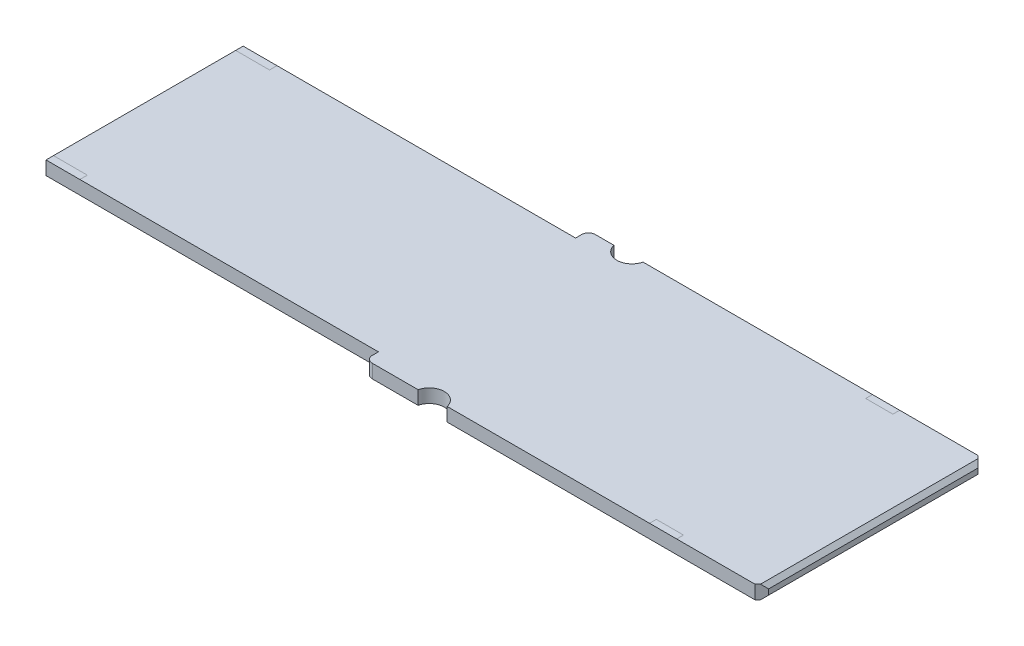
SolidWorks part; units mm, degrees
ref_plane "Front Plane" through (0, 0, 0) normal (0, 0, 1) x (1, 0, 0)
ref_plane "Top Plane" through (0, 0, 0) normal (0, 1, 0) x (1, 0, 0)
ref_plane "Right Plane" through (0, 0, 0) normal (1, 0, 0) x (0, 0, -1)
sketch "Sketch1" plane through (0, 0, 0) normal (0, 1, 0) x (1, 0, 0)
  line L0 (0, 7.25) -> (0, -7.25)
  line L1 (0, -7.25) -> (24.45, -7.25)
  line L2 (24.45, -7.25) -> (24.45, -8.2)
  line L3 (24.45, -8.2) -> (53.6, -8.2)
  line L4 (53.6, -8.2) -> (53.6, 8.2)
  line L5 (53.6, 8.2) -> (24.45, 8.2)
  line L6 (24.45, 7.25) -> (0, 7.25)
  line L7 (24.45, 8.2) -> (24.45, 7.25)
  dimension "D1" = 53.6
  dimension "D2" = 14.5
  dimension "D3" = 16.4
  dimension "D4" = 29.15
extrude "Boss-Extrude1" add sketch "Sketch1" along normal mid plane 1
chamfer "Chamfer2" [suppressed] distance 1 angle 45
chamfer "Chamfer3" distance 0.5 angle 45 2 edges at (53.6, 0, -8.2) (53.6, 0, 8.2)
sketch "Sketch2" plane through (0, -0.5, 0) normal (0, -1, 0) x (1, 0, 0)
  circle A0 centre (29.39, 8.45) radius 1.1
  circle A1 centre (27.39, -8.45) radius 1.1
  arc A2 (28.4317, 8.1643) -> (30.3483, 8.1643) centre (29.39, 8.45) ccw construction
  arc A3 (28.3483, -8.1643) -> (26.4317, -8.1643) centre (27.39, -8.45) ccw construction
  dimension "D1" = 2.2
extrude "Cut-Extrude1" cut sketch "Sketch2" against normal through all
sketch "Sketch3" plane through (0, 0.5, 0) normal (0, 1, 0) x (1, 0, 0)
  line L0 (53.6, -7.7) -> (53.6, 7.7) construction
  line L1 (53.6, 7.1) -> (45.6, 7.1)
  line L2 (53.6, 7.1) -> (53.6, 6.1)
  line L3 (53.6, 6.1) -> (45.6, 6.1)
  line L4 (45.6, 7.1) -> (45.6, 6.1)
  line L5 (53.1, 8.2) -> (28.4612, 8.2) construction
  dimension "D1" = 1
  dimension "D2" = 8
  dimension "D3" = 1.1
extrude "Cut-Extrude2" [suppressed] cut sketch "Sketch3" against normal blind 0.0001
pattern_linear "LPattern1" [suppressed] count 12 spacing 1.2
mirror "Mirror1" [suppressed] about plane through (0, 0, 0) normal (0, 1, 0)
sketch "Sketch4" plane through (0, -0.5, 0) normal (0, 1, 0) x (1, 0, 0)
  line L0 (25, 1.5) -> (25, -1.5) construction
  line L1 (23.5, 5) -> (26.5, 5)
  line L2 (23.5, 5) -> (23.5, 1.5)
  line L3 (23.5, 1.5) -> (26.5, 1.5)
  line L4 (26.5, 5) -> (26.5, 1.5)
  line L5 (23.5, -1.5) -> (26.5, -1.5)
  line L6 (23.5, -1.5) -> (23.5, -3.5)
  line L7 (23.5, -3.5) -> (26.5, -3.5)
  line L8 (26.5, -1.5) -> (26.5, -3.5)
  line L9 (25, 0) -> (0, 0) construction
  line L10 (7.45, 3.25) -> (23.5, 3.25) construction
  line L11 (4.45, 4.25) -> (7.45, 4.25)
  line L12 (4.45, 4.25) -> (4.45, 2.25)
  line L13 (4.45, 2.25) -> (7.45, 2.25)
  line L14 (7.45, 4.25) -> (7.45, 2.25)
  line L15 (0, 7.25) -> (0, -7.25) construction
  dimension "D1" = 3
  dimension "D2" = 3.5
  dimension "D3" = 2
  dimension "D4" = 3
  dimension "D5" = 25
  dimension "D6" = 4.45
extrude "Boss-Extrude2" [suppressed] add sketch "Sketch4" against normal blind 1
sketch "Sketch5" [suppressed] plane through (0, -0.525, 0) normal (0, 1, 0) x (1, 0, 0)
  line L0 (26.5, 1.5) -> (26.5, 5) construction
  line L1 (26.5, 5) -> (27.9, 5)
  line L2 (26.5, 5) -> (26.5, 4.7)
  line L3 (26.5, 4.7) -> (27.9, 4.7)
  line L4 (27.9, 5) -> (27.9, 4.7)
  line L5 (23.5, 5) -> (22.1, 5)
  line L6 (23.5, 5) -> (23.5, 4.7)
  line L7 (23.5, 4.7) -> (22.1, 4.7)
  line L8 (22.1, 5) -> (22.1, 4.7)
  line L9 (23.5, 5) -> (23.5, 1.5) construction
  line L10 (26.5, 4.6) -> (27.9, 4.6)
  line L11 (26.5, 4.6) -> (26.5, 4.3)
  line L12 (26.5, 4.3) -> (27.9, 4.3)
  line L13 (27.9, 4.6) -> (27.9, 4.3)
  line L14 (23.5, 4.6) -> (22.1, 4.6)
  line L15 (23.5, 4.6) -> (23.5, 4.3)
  line L16 (23.5, 4.3) -> (22.1, 4.3)
  line L17 (22.1, 4.6) -> (22.1, 4.3)
  line L18 (26.5, 4.2) -> (27.9, 4.2)
  line L19 (26.5, 4.2) -> (26.5, 3.9)
  line L20 (26.5, 3.9) -> (27.9, 3.9)
  line L21 (27.9, 4.2) -> (27.9, 3.9)
  line L22 (23.5, 4.2) -> (22.1, 4.2)
  line L23 (23.5, 4.2) -> (23.5, 3.9)
  line L24 (23.5, 3.9) -> (22.1, 3.9)
  line L25 (22.1, 4.2) -> (22.1, 3.9)
  line L26 (26.5, 3.8) -> (27.9, 3.8)
  line L27 (26.5, 3.8) -> (26.5, 3.5)
  line L28 (26.5, 3.5) -> (27.9, 3.5)
  line L29 (27.9, 3.8) -> (27.9, 3.5)
  line L30 (23.5, 3.8) -> (22.1, 3.8)
  line L31 (23.5, 3.8) -> (23.5, 3.5)
  line L32 (23.5, 3.5) -> (22.1, 3.5)
  line L33 (22.1, 3.8) -> (22.1, 3.5)
  line L34 (26.5, 3.4) -> (27.9, 3.4)
  line L35 (26.5, 3.4) -> (26.5, 3.1)
  line L36 (26.5, 3.1) -> (27.9, 3.1)
  line L37 (27.9, 3.4) -> (27.9, 3.1)
  line L38 (23.5, 3.4) -> (22.1, 3.4)
  line L39 (23.5, 3.4) -> (23.5, 3.1)
  line L40 (23.5, 3.1) -> (22.1, 3.1)
  line L41 (22.1, 3.4) -> (22.1, 3.1)
  line L42 (26.5, 3) -> (27.9, 3)
  line L43 (26.5, 3) -> (26.5, 2.7)
  line L44 (26.5, 2.7) -> (27.9, 2.7)
  line L45 (27.9, 3) -> (27.9, 2.7)
  line L46 (23.5, 3) -> (22.1, 3)
  line L47 (23.5, 3) -> (23.5, 2.7)
  line L48 (23.5, 2.7) -> (22.1, 2.7)
  line L49 (22.1, 3) -> (22.1, 2.7)
  line L50 (26.5, 2.6) -> (27.9, 2.6)
  line L51 (26.5, 2.6) -> (26.5, 2.3)
  line L52 (26.5, 2.3) -> (27.9, 2.3)
  line L53 (27.9, 2.6) -> (27.9, 2.3)
  line L54 (23.5, 2.6) -> (22.1, 2.6)
  line L55 (23.5, 2.6) -> (23.5, 2.3)
  line L56 (23.5, 2.3) -> (22.1, 2.3)
  line L57 (22.1, 2.6) -> (22.1, 2.3)
  line L58 (26.5, 2.2) -> (27.9, 2.2)
  line L59 (26.5, 2.2) -> (26.5, 1.9)
  line L60 (26.5, 1.9) -> (27.9, 1.9)
  line L61 (27.9, 2.2) -> (27.9, 1.9)
  line L62 (23.5, 2.2) -> (22.1, 2.2)
  line L63 (23.5, 2.2) -> (23.5, 1.9)
  line L64 (23.5, 1.9) -> (22.1, 1.9)
  line L65 (22.1, 2.2) -> (22.1, 1.9)
  line L66 (26.5, 1.8) -> (27.9, 1.8)
  line L67 (26.5, 1.8) -> (26.5, 1.5)
  line L68 (26.5, 1.5) -> (27.9, 1.5)
  line L69 (27.9, 1.8) -> (27.9, 1.5)
  line L70 (23.5, 1.8) -> (22.1, 1.8)
  line L71 (23.5, 1.8) -> (23.5, 1.5)
  line L72 (23.5, 1.5) -> (22.1, 1.5)
  line L73 (22.1, 1.8) -> (22.1, 1.5)
  line L74 (26.5, -1.9) -> (27.9, -1.9)
  line L75 (26.5, -1.5) -> (27.9, -1.5)
  line L76 (26.5, -1.5) -> (26.5, -1.8)
  line L77 (26.5, -1.8) -> (27.9, -1.8)
  line L78 (27.9, -1.5) -> (27.9, -1.8)
  line L79 (23.5, -1.5) -> (22.1, -1.5)
  line L80 (23.5, -1.5) -> (23.5, -1.8)
  line L81 (23.5, -1.8) -> (22.1, -1.8)
  line L82 (22.1, -1.5) -> (22.1, -1.8)
  line L83 (26.5, -1.9) -> (26.5, -2.2)
  line L84 (26.5, -2.2) -> (27.9, -2.2)
  line L85 (27.9, -1.9) -> (27.9, -2.2)
  line L86 (23.5, -1.9) -> (22.1, -1.9)
  line L87 (23.5, -1.9) -> (23.5, -2.2)
  line L88 (23.5, -2.2) -> (22.1, -2.2)
  line L89 (22.1, -1.9) -> (22.1, -2.2)
  line L90 (26.5, -2.3) -> (27.9, -2.3)
  line L91 (26.5, -2.3) -> (26.5, -2.6)
  line L92 (26.5, -2.6) -> (27.9, -2.6)
  line L93 (27.9, -2.3) -> (27.9, -2.6)
  line L94 (23.5, -2.3) -> (22.1, -2.3)
  line L95 (23.5, -2.3) -> (23.5, -2.6)
  line L96 (23.5, -2.6) -> (22.1, -2.6)
  line L97 (22.1, -2.3) -> (22.1, -2.6)
  line L98 (26.5, -2.7) -> (27.9, -2.7)
  line L99 (26.5, -2.7) -> (26.5, -3)
  line L100 (26.5, -3) -> (27.9, -3)
  line L101 (27.9, -2.7) -> (27.9, -3)
  line L102 (23.5, -2.7) -> (22.1, -2.7)
  line L103 (23.5, -2.7) -> (23.5, -3)
  line L104 (23.5, -3) -> (22.1, -3)
  line L105 (22.1, -2.7) -> (22.1, -3)
  line L106 (26.5, -3.1) -> (27.9, -3.1)
  line L107 (26.5, -3.1) -> (26.5, -3.4)
  line L108 (26.5, -3.4) -> (27.9, -3.4)
  line L109 (27.9, -3.1) -> (27.9, -3.4)
  line L110 (23.5, -3.1) -> (22.1, -3.1)
  line L111 (23.5, -3.1) -> (23.5, -3.4)
  line L112 (23.5, -3.4) -> (22.1, -3.4)
  line L113 (22.1, -3.1) -> (22.1, -3.4)
  line L115 (7.45, 3.85) -> (8.85, 3.85)
  line L116 (7.45, 4.25) -> (8.85, 4.25)
  line L117 (7.45, 4.25) -> (7.45, 3.95)
  line L118 (7.45, 3.95) -> (8.85, 3.95)
  line L119 (8.85, 4.25) -> (8.85, 3.95)
  line L120 (4.45, 4.25) -> (3.05, 4.25)
  line L121 (4.45, 4.25) -> (4.45, 3.95)
  line L122 (4.45, 3.95) -> (3.05, 3.95)
  line L123 (3.05, 4.25) -> (3.05, 3.95)
  line L124 (7.45, 3.85) -> (7.45, 3.55)
  line L125 (7.45, 3.55) -> (8.85, 3.55)
  line L126 (8.85, 3.85) -> (8.85, 3.55)
  line L127 (4.45, 3.85) -> (3.05, 3.85)
  line L128 (4.45, 3.85) -> (4.45, 3.55)
  line L129 (4.45, 3.55) -> (3.05, 3.55)
  line L130 (3.05, 3.85) -> (3.05, 3.55)
  line L131 (7.45, 3.45) -> (8.85, 3.45)
  line L132 (7.45, 3.45) -> (7.45, 3.15)
  line L133 (7.45, 3.15) -> (8.85, 3.15)
  line L134 (8.85, 3.45) -> (8.85, 3.15)
  line L135 (4.45, 3.45) -> (3.05, 3.45)
  line L136 (4.45, 3.45) -> (4.45, 3.15)
  line L137 (4.45, 3.15) -> (3.05, 3.15)
  line L138 (3.05, 3.45) -> (3.05, 3.15)
  line L139 (7.45, 3.05) -> (8.85, 3.05)
  line L140 (7.45, 3.05) -> (7.45, 2.75)
  line L141 (7.45, 2.75) -> (8.85, 2.75)
  line L142 (8.85, 3.05) -> (8.85, 2.75)
  line L143 (4.45, 3.05) -> (3.05, 3.05)
  line L144 (4.45, 3.05) -> (4.45, 2.75)
  line L145 (4.45, 2.75) -> (3.05, 2.75)
  line L146 (3.05, 3.05) -> (3.05, 2.75)
  line L147 (7.45, 2.65) -> (8.85, 2.65)
  line L148 (7.45, 2.65) -> (7.45, 2.35)
  line L149 (7.45, 2.35) -> (8.85, 2.35)
  line L150 (8.85, 2.65) -> (8.85, 2.35)
  line L151 (4.45, 2.65) -> (3.05, 2.65)
  line L152 (4.45, 2.65) -> (4.45, 2.35)
  line L153 (4.45, 2.35) -> (3.05, 2.35)
  line L154 (3.05, 2.65) -> (3.05, 2.35)
  dimension "D1" = 1.4
  dimension "D2" = 1.4
  dimension "D3" = 0.3
  dimension "D6" = 1.4
  dimension "D4" = 9
  dimension "D5" = 5
  dimension "D7" = 5
extrude "Boss-Extrude3" [suppressed] add sketch "Sketch5" against normal blind 0.001
sketch "Sketch6" plane through (0, -0.5, 0) normal (0, 1, 0) x (1, 0, 0)
  line L0 (0, 7.25) -> (0, -7.25) construction
  line L1 (9.75, -5) -> (12.25, -5)
  line L2 (9.75, -5) -> (9.75, -2.5)
  line L3 (9.75, -2.5) -> (12.25, -2.5)
  line L4 (12.25, -5) -> (12.25, -2.5)
  line L5 (9.75, -5) -> (12.25, -2.5) construction
  line L6 (9.75, -2.5) -> (12.25, -5) construction
  line L7 (0, -7.25) -> (24.45, -7.25) construction
  point P0 (11, -3.75)
  dimension "D1" = 2.5
  dimension "D2" = 2.5
  dimension "D3" = 11
  dimension "D4" = 3.5
extrude "Boss-Extrude4" [suppressed] add sketch "Sketch6" against normal blind 1.9
sketch "Sketch7" plane through (0, 0.5, 0) normal (0, -1, 0) x (1, 0, 0)
  line L1 (3.3061, 4.676) -> (8.8061, 4.676)
  line L2 (3.3061, 4.676) -> (3.3061, 2.676)
  line L3 (3.3061, 2.676) -> (8.8061, 2.676)
  line L4 (8.8061, 4.676) -> (8.8061, 2.676)
  line L5 (3.3061, 4.676) -> (8.8061, 2.676) construction
  line L6 (3.3061, 2.676) -> (8.8061, 4.676) construction
  line L7 (3.3061, 1) -> (8.8061, 1)
  line L8 (3.3061, 1) -> (3.3061, -1)
  line L9 (3.3061, -1) -> (8.8061, -1)
  line L10 (8.8061, 1) -> (8.8061, -1)
  line L11 (3.3061, 1) -> (8.8061, -1) construction
  line L12 (3.3061, -1) -> (8.8061, 1) construction
  line L13 (3.3061, -2.6873) -> (8.8061, -2.6873)
  line L14 (3.3061, -2.6873) -> (3.3061, -4.6873)
  line L15 (3.3061, -4.6873) -> (8.8061, -4.6873)
  line L16 (8.8061, -2.6873) -> (8.8061, -4.6873)
  line L17 (3.3061, -2.6873) -> (8.8061, -4.6873) construction
  line L18 (3.3061, -4.6873) -> (8.8061, -2.6873) construction
  point P0 (6.0561, 3.676)
  point P5 (6.0561, 0)
  point P10 (6.0561, -3.6873)
  dimension "D1" = 5.5
  dimension "D2" = 2
extrude "Boss-Extrude5" [suppressed] add sketch "Sketch7" against normal blind 1
fillet "Fillet1" radius 0.5 2 edges at (24.45, 0, 8.2) (24.45, 0, -8.2)
sketch "Sketch8" plane through (0, 0.5, 0) normal (0, 1, 0) x (1, 0, 0)
  line L0 (30.4612, -8.2) -> (53.1, -8.2) construction
  line L1 (0, -7.25) -> (2.49, -7.25)
  line L2 (0, -7.25) -> (0, -6.7)
  line L3 (0, -6.7) -> (2.49, -6.7)
  line L4 (2.49, -7.25) -> (2.49, -6.7)
  line L5 (0, 7.25) -> (2.49, 7.25)
  line L6 (0, 7.25) -> (0, 6.7)
  line L7 (0, 6.7) -> (2.49, 6.7)
  line L8 (2.49, 7.25) -> (2.49, 6.7)
  line L9 (45.34, -7.7) -> (47.34, -7.7)
  line L10 (45.34, -7.7) -> (45.34, -8.2)
  line L11 (45.34, -8.2) -> (47.34, -8.2)
  line L12 (47.34, -7.7) -> (47.34, -8.2)
  line L13 (47.34, -7.7) -> (47.34, -8.45) construction
  line L14 (53.1, 8.2) -> (28.4612, 8.2) construction
  line L15 (45.34, 7.7) -> (47.34, 7.7)
  line L16 (45.34, 7.7) -> (45.34, 8.2)
  line L17 (45.34, 8.2) -> (47.34, 8.2)
  line L18 (47.34, 7.7) -> (47.34, 8.2)
  line L19 (47.34, 8.45) -> (47.34, 7.7) construction
extrude "Cut-Extrude3" cut sketch "Sketch8" against normal blind 0.0001
sketch "Sketch9" plane through (0, -0.5, 0) normal (0, -1, 0) x (1, 0, 0)
  line L50 (2.09, 7.425) -> (0.49, 7.425)
  line L51 (2.34, 6.925) -> (2.34, 7.175)
  line L52 (0.24, 7.175) -> (0.24, 6.925)
  line L53 (0.49, 6.675) -> (2.09, 6.675)
  line L54 (2.09, 7.425) -> (0.49, 7.425)
  line L55 (2.34, 6.925) -> (2.34, 7.175)
  line L56 (0.24, 7.175) -> (0.24, 6.925)
  line L57 (0.49, 6.675) -> (2.09, 6.675)
  line L74 (2.34, -7.175) -> (2.34, -6.925)
  line L75 (0.49, -7.425) -> (2.09, -7.425)
  line L76 (0.24, -6.925) -> (0.24, -7.175)
  line L77 (2.09, -6.675) -> (0.49, -6.675)
  line L78 (2.34, -7.175) -> (2.34, -6.925)
  line L79 (0.49, -7.425) -> (2.09, -7.425)
  line L80 (0.24, -6.925) -> (0.24, -7.175)
  line L81 (2.09, -6.675) -> (0.49, -6.675)
  line L111 (26.14, -8.125) -> (26.14, -7.575)
  line L112 (25.89, -7.325) -> (25.11, -7.325)
  line L113 (24.86, -7.575) -> (24.86, -8.125)
  line L114 (25.11, -8.375) -> (25.89, -8.375)
  line L115 (26.14, -8.125) -> (26.14, -7.575)
  line L116 (25.89, -7.325) -> (25.11, -7.325)
  line L117 (24.86, -7.575) -> (24.86, -8.125)
  line L118 (25.11, -8.375) -> (25.89, -8.375)
  line L135 (47.34, 8.2) -> (45.34, 8.2)
  line L136 (47.34, 8.2) -> (47.34, -8.2)
  line L137 (47.34, -8.2) -> (45.34, -8.2)
  line L138 (25.49, 7.325) -> (26.89, 7.325)
  line L139 (27.14, 7.575) -> (27.14, 8.125)
  line L140 (26.89, 8.375) -> (25.49, 8.375)
  line L141 (25.24, 8.125) -> (25.24, 7.575)
  line L142 (25.49, 7.325) -> (26.89, 7.325)
  line L143 (27.14, 7.575) -> (27.14, 8.125)
  line L144 (26.89, 8.375) -> (25.49, 8.375)
  line L145 (25.24, 8.125) -> (25.24, 7.575)
  line L146 (45.34, 8.2) -> (45.34, -8.2)
  arc A51 (0.49, 7.425) -> (0.24, 7.175) centre (0.49, 7.175) ccw
  arc A52 (2.34, 7.175) -> (2.09, 7.425) centre (2.09, 7.175) ccw
  arc A53 (2.09, 6.675) -> (2.34, 6.925) centre (2.09, 6.925) ccw
  arc A54 (0.24, 6.925) -> (0.49, 6.675) centre (0.49, 6.925) ccw
  arc A55 (0.49, 7.425) -> (0.24, 7.175) centre (0.49, 7.175) ccw
  arc A56 (2.34, 7.175) -> (2.09, 7.425) centre (2.09, 7.175) ccw
  arc A57 (2.09, 6.675) -> (2.34, 6.925) centre (2.09, 6.925) ccw
  arc A58 (0.24, 6.925) -> (0.49, 6.675) centre (0.49, 6.925) ccw
  arc A79 (2.09, -7.425) -> (2.34, -7.175) centre (2.09, -7.175) ccw
  arc A80 (0.24, -7.175) -> (0.49, -7.425) centre (0.49, -7.175) ccw
  arc A81 (2.34, -6.925) -> (2.09, -6.675) centre (2.09, -6.925) ccw
  arc A82 (0.49, -6.675) -> (0.24, -6.925) centre (0.49, -6.925) ccw
  arc A83 (2.09, -7.425) -> (2.34, -7.175) centre (2.09, -7.175) ccw
  arc A84 (0.24, -7.175) -> (0.49, -7.425) centre (0.49, -7.175) ccw
  arc A85 (2.34, -6.925) -> (2.09, -6.675) centre (2.09, -6.925) ccw
  arc A86 (0.49, -6.675) -> (0.24, -6.925) centre (0.49, -6.925) ccw
  arc A109 (25.89, -8.375) -> (26.14, -8.125) centre (25.89, -8.125) ccw
  arc A110 (26.14, -7.575) -> (25.89, -7.325) centre (25.89, -7.575) ccw
  arc A111 (25.11, -7.325) -> (24.86, -7.575) centre (25.11, -7.575) ccw
  arc A112 (24.86, -8.125) -> (25.11, -8.375) centre (25.11, -8.125) ccw
  arc A113 (25.89, -8.375) -> (26.14, -8.125) centre (25.89, -8.125) ccw
  arc A114 (26.14, -7.575) -> (25.89, -7.325) centre (25.89, -7.575) ccw
  arc A115 (25.11, -7.325) -> (24.86, -7.575) centre (25.11, -7.575) ccw
  arc A116 (24.86, -8.125) -> (25.11, -8.375) centre (25.11, -8.125) ccw
  arc A134 (25.24, 7.575) -> (25.49, 7.325) centre (25.49, 7.575) ccw
  arc A135 (26.89, 7.325) -> (27.14, 7.575) centre (26.89, 7.575) ccw
  arc A136 (27.14, 8.125) -> (26.89, 8.375) centre (26.89, 8.125) ccw
  arc A137 (25.49, 8.375) -> (25.24, 8.125) centre (25.49, 8.125) ccw
  arc A138 (25.24, 7.575) -> (25.49, 7.325) centre (25.49, 7.575) ccw
  arc A139 (26.89, 7.325) -> (27.14, 7.575) centre (26.89, 7.575) ccw
  arc A140 (27.14, 8.125) -> (26.89, 8.375) centre (26.89, 8.125) ccw
  arc A141 (25.49, 8.375) -> (25.24, 8.125) centre (25.49, 8.125) ccw
  dimension "D1" = 0.05
  dimension "D2" = 0.05
  dimension "D3" = 0.05
  dimension "D4" = 0.05
extrude "Cut-Extrude4" cut sketch "Sketch9" against normal blind 0.0001
chamfer "Chamfer4" distance 0.3 angle 45 2 edges at (53.6, 0.5, 0) (53.6, -0.5, 0)
